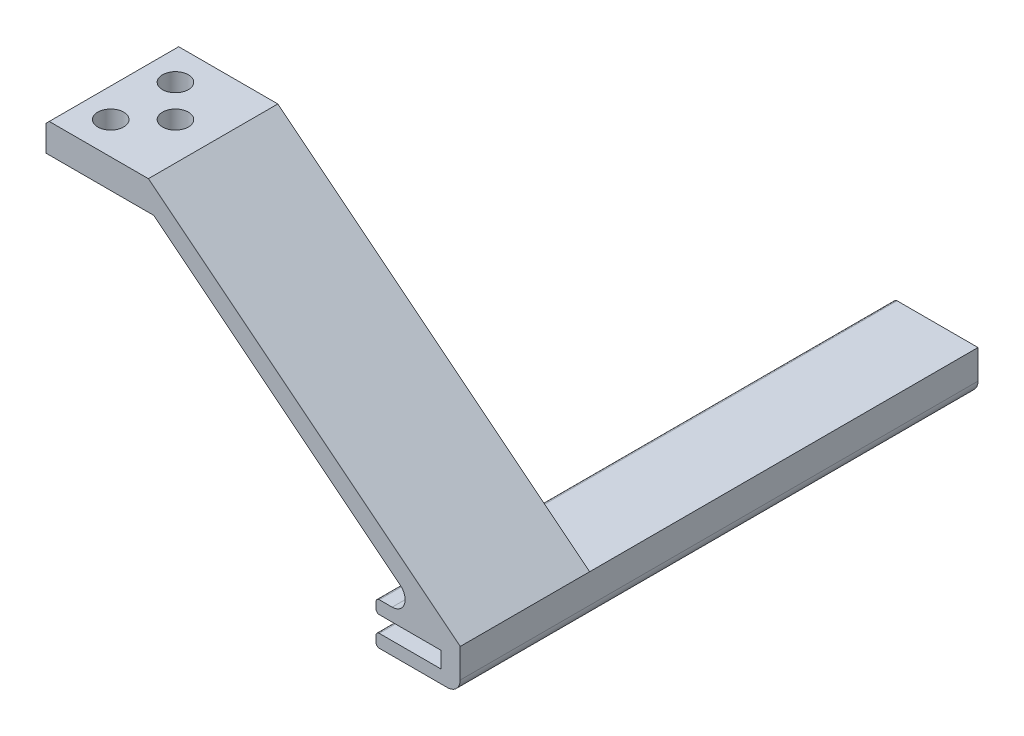
SolidWorks part; units mm, degrees
material "PEI"
ref_plane "前视基准面" through (0, 0, 0) normal (0, 0, 1) x (1, 0, 0)
ref_plane "上视基准面" through (0, 0, 0) normal (0, 1, 0) x (1, 0, 0)
ref_plane "右视基准面" through (0, 0, 0) normal (1, 0, 0) x (0, 0, -1)
other "Configuration Table"
sketch "草图1" plane through (0, 0, 0) normal (0, 0, 1) x (1, 0, 0)
  line L0 (0, -10.6875) -> (0, 21.8964) construction
  line L1 (51.5, 0) -> (62, 0)
  line L2 (64, 2) -> (64, 6.5)
  line L3 (53.4874, 6.5) -> (51.5, 6.5)
  line L4 (51, 6) -> (51, 5)
  line L5 (51.5, 4.5) -> (61, 4.5)
  line L6 (61, 4.5) -> (61, 2)
  line L7 (61, 2) -> (51.5, 2)
  line L8 (51, 1.5) -> (51, 0.5)
  line L9 (64, 6.5) -> (15.8184, 45)
  line L10 (15.8184, 45) -> (0, 45)
  line L11 (0, 45) -> (0, 40)
  line L12 (0, 40) -> (17.27, 40)
  line L13 (17.27, 40) -> (54.7359, 10.0625)
  arc A0 (53.4874, 6.5) -> (54.7359, 10.0625) centre (53.4874, 8.5) ccw
  arc A1 (62, 0) -> (64, 2) centre (62, 2) ccw
  arc A2 (51, 0.5) -> (51.5, 0) centre (51.5, 0.5) ccw
  arc A3 (51, 1.5) -> (51.5, 2) centre (51.5, 1.5) cw
  arc A4 (51.5, 4.5) -> (51, 5) centre (51.5, 5) cw
  arc A5 (51.5, 6.5) -> (51, 6) centre (51.5, 6) ccw
  point P5 (61, 3.25)
  point P21 (64, 0)
  point P24 (51, 0)
  point P27 (51, 2)
  point P30 (51, 4.5)
  point P33 (51, 6.5)
  dimension "D12" = 2
  dimension "D13" = 0.5
  dimension "D1" = 2
  dimension "D2" = 2.5
  dimension "D3" = 2
  dimension "D4" = 3
  dimension "D5" = 13
  dimension "D6" = 13
  dimension "D7" = 3
  dimension "D8" = 5
  dimension "D9" = 40
  dimension "D10" = 17.27
  dimension "D11" = 61
extrude "凸台-拉伸1" add sketch "草图1" along normal blind 20
sketch "草图2" plane through (0, 0, 0) normal (0, -1, 0) x (1, 0, 0)
  line L0 (51.5, 20) -> (62, 20) construction
  line L1 (61, 20) -> (61, 0) construction
  line L2 (51.5, 20) -> (62, 20)
  line L3 (61, 20) -> (61, 0)
  line L4 (51, 20) -> (51, 0) construction
  line L5 (51, 20) -> (51, 0)
  line L6 (57, 16.5) -> (51, 16.5)
  line L7 (57, 11.5) -> (51, 11.5)
  circle A0 centre (57, 14) radius 2.5
  line M7 (51.5, 20) -> (51.5, 0)
  dimension "D1" = 5
  dimension "D2" = 4
  dimension "D3" = 6
extrude "切除-拉伸1" cut sketch "草图2" against normal blind 7 contours A0 | A0 L6 L7 M7 | L7 L6 L5 M7
fillet "圆角2" radius 1 1 edges at (54.8103, 7, 14)
sketch "草图3" plane through (0, 0, 0) normal (0, 0, -1) x (-1, 0, 0)
  line L0 (-64, 6.5) -> (-53.4874, 6.5)
  line L13 (-15.8184, 45) -> (-64, 6.5)
  line L14 (-64, 6.5) -> (-64, 2)
  line L15 (-62, 0) -> (-51.5, 0)
  line L16 (-51, 0.5) -> (-51, 1.5)
  line L17 (-51.5, 2) -> (-61, 2)
  line L18 (-61, 2) -> (-61, 4.5)
  line L19 (-61, 4.5) -> (-51.5, 4.5)
  line L20 (-51, 5) -> (-51, 6)
  line L21 (-51.5, 6.5) -> (-53.4874, 6.5)
  line L22 (-54.7359, 10.0625) -> (-17.27, 40)
  line L23 (-17.27, 40) -> (0, 40)
  line L24 (0, 40) -> (0, 45)
  line L25 (0, 45) -> (-15.8184, 45)
  line L27 (-64, 6.5) -> (-64, 2)
  line L28 (-62, 0) -> (-51.5, 0)
  line L29 (-51, 0.5) -> (-51, 1.5)
  line L30 (-51.5, 2) -> (-61, 2)
  line L31 (-61, 2) -> (-61, 4.5)
  line L32 (-61, 4.5) -> (-51.5, 4.5)
  line L33 (-51, 5) -> (-51, 6)
  line L34 (-51.5, 6.5) -> (-53.4874, 6.5)
  arc A6 (-64, 2) -> (-62, 0) centre (-62, 2) ccw
  arc A7 (-51.5, 0) -> (-51, 0.5) centre (-51.5, 0.5) ccw
  arc A8 (-51, 1.5) -> (-51.5, 2) centre (-51.5, 1.5) ccw
  arc A9 (-51.5, 4.5) -> (-51, 5) centre (-51.5, 5) ccw
  arc A10 (-51, 6) -> (-51.5, 6.5) centre (-51.5, 6) ccw
  arc A11 (-54.7359, 10.0625) -> (-53.4874, 6.5) centre (-53.4874, 8.5) ccw
  arc A12 (-64, 2) -> (-62, 0) centre (-62, 2) ccw
  arc A13 (-51.5, 0) -> (-51, 0.5) centre (-51.5, 0.5) ccw
  arc A14 (-51, 1.5) -> (-51.5, 2) centre (-51.5, 1.5) ccw
  arc A15 (-51.5, 4.5) -> (-51, 5) centre (-51.5, 5) ccw
  arc A16 (-51, 6) -> (-51.5, 6.5) centre (-51.5, 6) ccw
  dimension "D1" = 0
extrude "凸台-拉伸2" add sketch "草图3" along normal blind 60
sketch "草图4" plane through (0, 45, 0) normal (0, 1, 0) x (1, 0, 0)
  line L0 (0, -20) -> (0, 0) construction
  line L1 (15.8184, -20) -> (0, -20) construction
  circle A0 centre (5, -5) radius 2
  circle A1 centre (5, -15) radius 2
  circle A2 centre (10, -10) radius 2
  point P10 (6.3379, -11.0376)
  point P13 (10.8226, -8)
  dimension "D1" = 4
  dimension "D2" = 4
  dimension "D3" = 4
  dimension "D4" = 5
  dimension "D5" = 5
  dimension "D6" = 10
  dimension "D7" = 5
  dimension "D8" = 10
  dimension "D9" = 10
extrude "切除-拉伸2" cut sketch "草图4" against normal up to surface (5 mm away) up to face at (8.635, 40, 10)
chamfer "倒角1" distance 0.5 angle 45 4 edges at (8.635, 40, 20) (8.635, 40, 0) (0, 40, 10) (0, 45, 10)
